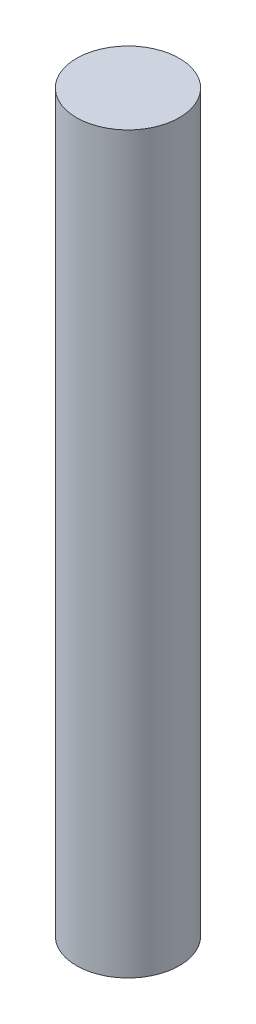
SolidWorks part; units mm, degrees
material "6063-O, pręt wytłaczany (SS)"
ref_plane "Płaszczyzna przednia" through (0, 0, 0) normal (0, 0, 1) x (1, 0, 0)
ref_plane "Płaszczyzna górna" through (0, 0, 0) normal (0, 1, 0) x (1, 0, 0)
ref_plane "Płaszczyzna prawa" through (0, 0, 0) normal (1, 0, 0) x (0, 0, -1)
sketch "Szkic2" plane through (0, 0, 0) normal (0, 1, 0) x (1, 0, 0)
  circle A0 centre (0, 0) radius 35
  dimension "D1" = 70
extrude "Dodanie-wyciągnięcie1" add sketch "Szkic2" along normal blind 500
